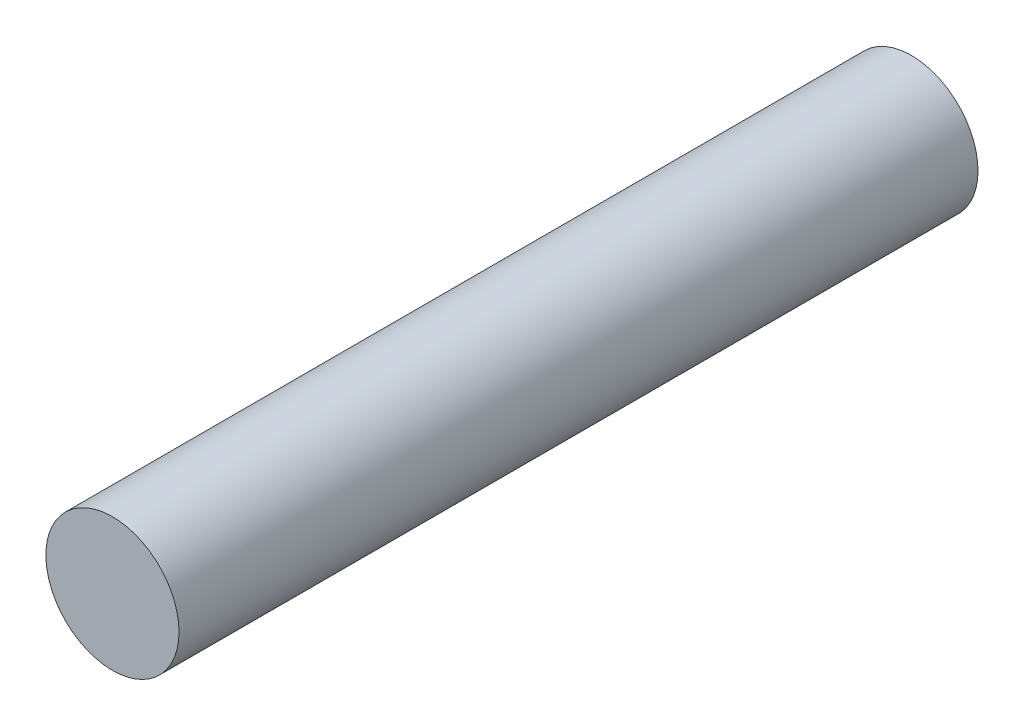
SolidWorks part; units mm, degrees
ref_plane "前视基准面" through (0, 0, 0) normal (0, 0, 1) x (1, 0, 0)
ref_plane "上视基准面" through (0, 0, 0) normal (0, 1, 0) x (1, 0, 0)
ref_plane "右视基准面" through (0, 0, 0) normal (1, 0, 0) x (0, 0, -1)
other "Configuration Table"
sketch "草图1" plane through (0, 0, 0) normal (0, 0, 1) x (1, 0, 0)
  circle A0 centre (0, 0) radius 2.5
  dimension "D1" = 5
extrude "凸台-拉伸1" add sketch "草图1" along normal blind 30
